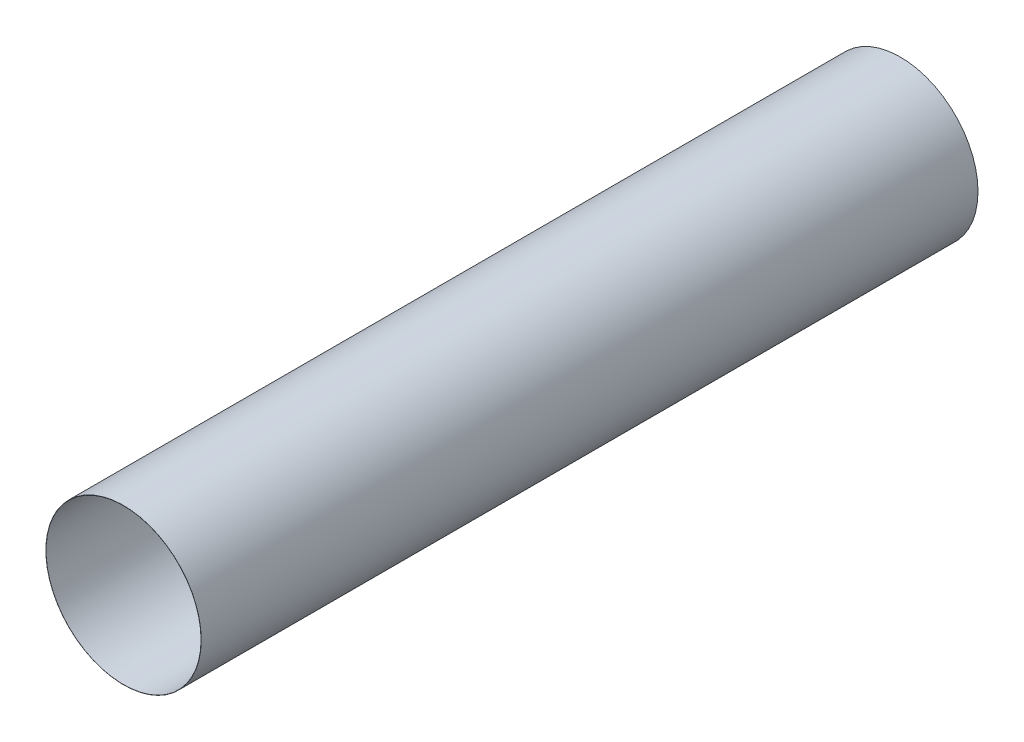
SolidWorks part; units mm, degrees
ref_plane "Front Plane" through (0, 0, 0) normal (0, 0, 1) x (1, 0, 0)
ref_plane "Top Plane" through (0, 0, 0) normal (0, 1, 0) x (1, 0, 0)
ref_plane "Right Plane" through (0, 0, 0) normal (1, 0, 0) x (0, 0, -1)
sketch "Sketch2" plane through (0, 0, 0) normal (0, 0, 1) x (1, 0, 0)
  circle A0 centre (0, 0) radius 1000
  circle A1 centre (0, 0) radius 998
extrude "Boss-Extrude1" add sketch "Sketch2" along normal blind 10000
